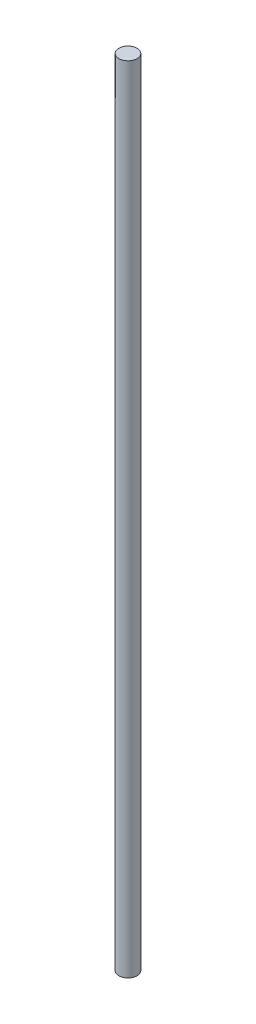
SolidWorks part; units mm, degrees
ref_plane "Plan de face" through (0, 0, 0) normal (0, 0, 1) x (1, 0, 0)
ref_plane "Plan de dessus" through (0, 0, 0) normal (0, 1, 0) x (1, 0, 0)
ref_plane "Plan de droite" through (0, 0, 0) normal (1, 0, 0) x (0, 0, -1)
sketch "Esquisse1" plane through (0, 0, 0) normal (0, 1, 0) x (1, 0, 0)
  circle A0 centre (0, 0) radius 3
  dimension "D1" = 6
extrude "Boss.-Extru.1" add sketch "Esquisse1" along normal blind 263
